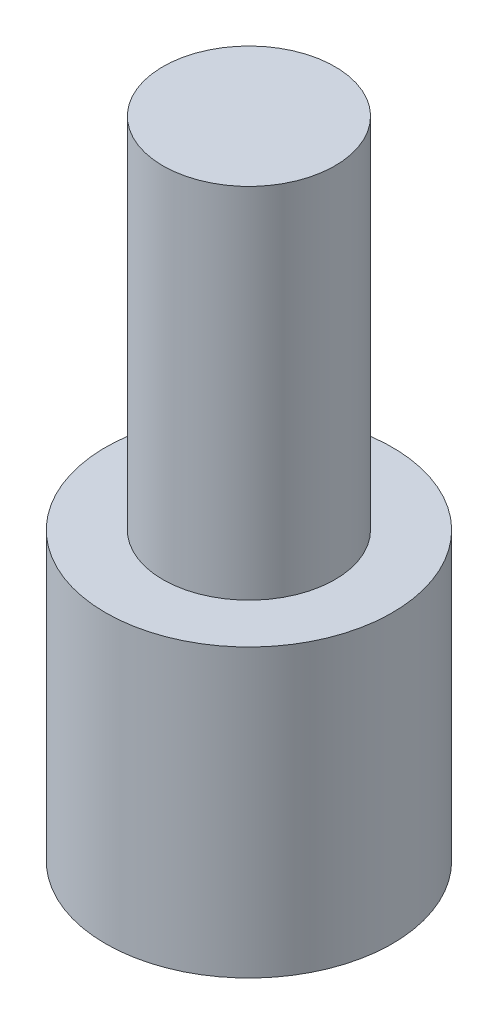
SolidWorks part; units mm, degrees
ref_plane "Front Plane" through (0, 0, 0) normal (0, 0, 1) x (1, 0, 0)
ref_plane "Top Plane" through (0, 0, 0) normal (0, 1, 0) x (1, 0, 0)
ref_plane "Right Plane" through (0, 0, 0) normal (1, 0, 0) x (0, 0, -1)
sketch "Sketch1" plane through (0, 0, 0) normal (0, 1, 0) x (1, 0, 0)
  circle A0 centre (0, 0) radius 5
  dimension "D1" = 10
extrude "Boss-Extrude1" add sketch "Sketch1" along normal blind 10 contours A0
sketch "Sketch2" plane through (0, 0, 0) normal (0, -1, 0) x (1, 0, 0)
  circle A0 centre (0, 0) radius 2.5
  dimension "D1" = 5
extrude "Cut-Extrude1" cut sketch "Sketch2" against normal blind 8
sketch "Sketch3" plane through (0, 10, 0) normal (0, 1, 0) x (1, 0, 0)
  circle A0 centre (0, 0) radius 3
  dimension "D1" = 6
extrude "Boss-Extrude2" add sketch "Sketch3" along normal blind 12.5 contours A0
